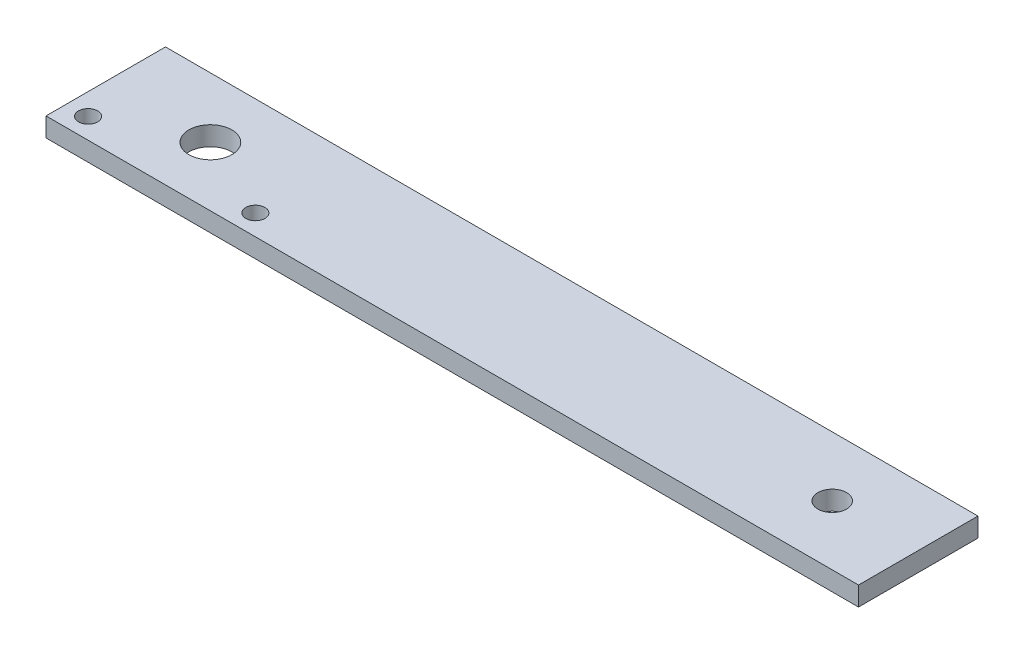
SolidWorks part; units mm, degrees
ref_plane "Front Plane" through (0, 0, 0) normal (0, 0, 1) x (1, 0, 0)
ref_plane "Top Plane" through (0, 0, 0) normal (0, 1, 0) x (1, 0, 0)
ref_plane "Right Plane" through (0, 0, 0) normal (1, 0, 0) x (0, 0, -1)
sketch "Sketch1" plane through (0, 0, 0) normal (0, 1, 0) x (1, 0, 0)
  line L1 (-85, 12.5) -> (85, 12.5)
  line L2 (-85, 12.5) -> (-85, -12.5)
  line L3 (-85, -12.5) -> (85, -12.5)
  line L4 (85, 12.5) -> (85, -12.5)
  line L5 (-85, 12.5) -> (85, -12.5) construction
  line L6 (-85, -12.5) -> (85, 12.5) construction
  circle A0 centre (-63.0312, -0.0802) radius 4.5
  circle A1 centre (-63.0095, -7.0801) radius 14
  circle A2 centre (-80.5095, -8.1827) radius 2
  circle A3 centre (-45.5095, -8.1827) radius 2
  circle A4 centre (67, 0) radius 3
  point P0 (0, 0)
  point P16 (0, 0)
  point P17 (85, 0)
  dimension "D3" = 18
  dimension "D1" = 25
  dimension "D2" = 170
extrude "Boss-Extrude1" add sketch "Sketch1" along normal blind 4 contours A1 L3 L4 L1 L2 A4 A3 A2 | L3 A1 A0
